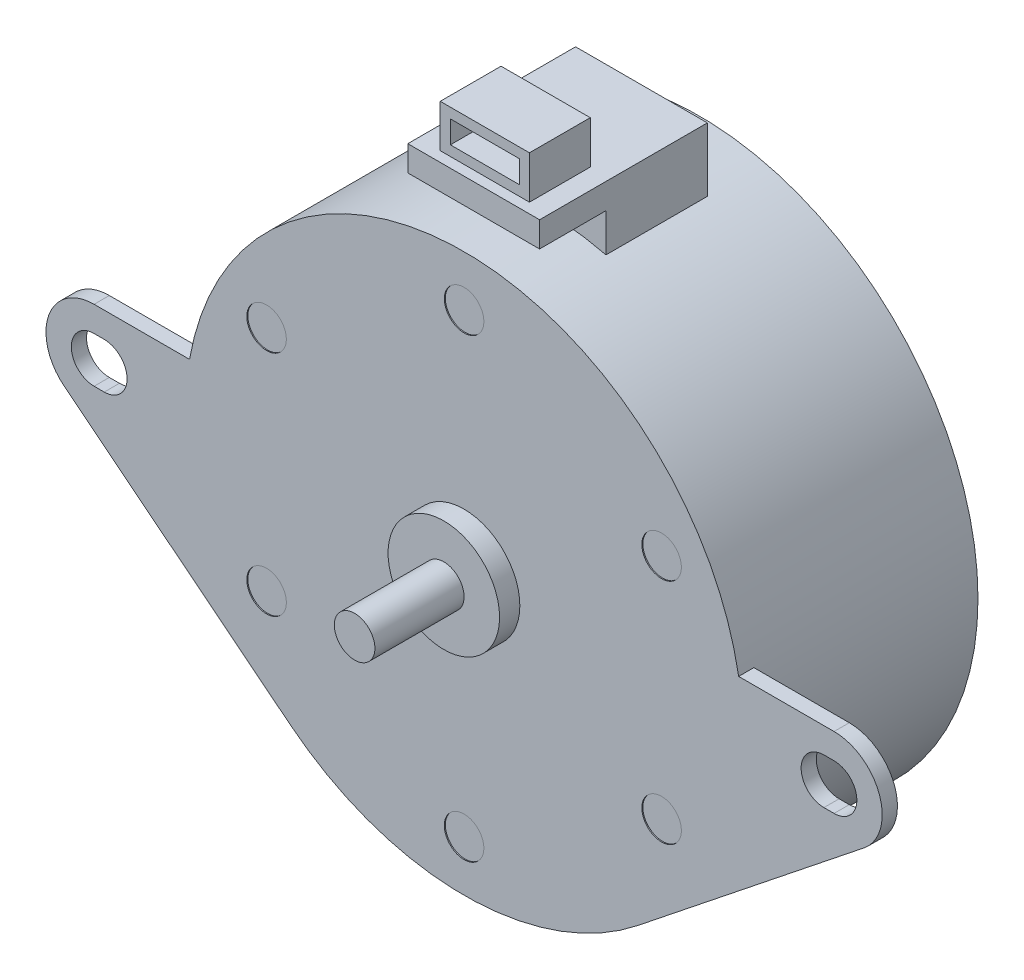
SolidWorks part; units mm, degrees
ref_plane "Front Plane" through (0, 0, 0) normal (0, 0, 1) x (1, 0, 0)
ref_plane "Top Plane" through (0, 0, 0) normal (0, 1, 0) x (1, 0, 0)
ref_plane "Right Plane" through (0, 0, 0) normal (1, 0, 0) x (0, 0, -1)
ref_plane "Plane1" through (0, 27.5, 0) normal (0, -1, 0) x (1, 0, 0)
sketch "Sketch1" plane through (0, 27.5, 0) normal (0, -1, 0) x (1, 0, 0)
  line L0 (55, 23.2) -> (27.5, 23.2)
  line L1 (27.5, 23.2) -> (27.5, 0)
  line L2 (27.5, 0) -> (55, 0)
  line L3 (55, 0) -> (55, 23.2)
  line L4 (27.5, 23.2) -> (27.5, 0) construction
revolve "Revolve1" add sketch "Sketch1" angle 360 about L4
ref_plane "Plane2" through (0, 60.5, 0) normal (0, 1, 0) x (1, 0, 0)
sketch "Sketch2" plane through (0, 60.5, 0) normal (0, 1, 0) x (1, 0, 0)
  line L0 (21, -5.7) -> (21, -15.7)
  line L1 (21, -15.7) -> (34, -15.7)
  line L2 (34, -15.7) -> (34, -5.7)
  line L3 (34, -5.7) -> (21, -5.7)
extrude "Boss-Extrude1" add sketch "Sketch2" against normal up to next
sketch "Sketch3" plane through (0, 0, 15.7) normal (0, 0, 1) x (1, 0, 0)
  line L0 (34, 60.5) -> (34, 58)
  line L1 (21, 58) -> (21, 60.5)
  line L2 (21, 60.5) -> (34, 60.5)
  spline S0 degree 1 poles (21, 58) (34, 58) knots 0 0 1 1
extrude "Boss-Extrude2" add sketch "Sketch3" along normal blind 6.5533
ref_plane "Plane3" through (0, 0, 23.2) normal (0, 0, 1) x (1, 0, 0)
sketch "Sketch4" plane through (0, 0, 23.2) normal (0, 0, 1) x (1, 0, 0)
  line L0 (64, 32.25) -> (54.5867, 32.25)
  line L1 (44.6404, 5.9952) -> (66.9606, 23.7855)
  arc A0 (66.9606, 23.7855) -> (64, 32.25) centre (64, 27.5) ccw
  arc A1 (54.5867, 32.25) -> (44.6404, 5.9952) centre (27.5, 27.5) cw
extrude "Boss-Extrude3" add sketch "Sketch4" against normal blind 1.5
sketch "Sketch5" plane through (0, 0, 23.2) normal (0, 0, 1) x (1, 0, 0)
  line L0 (-11.9606, 23.7855) -> (10.3596, 5.9952)
  line L1 (0.4133, 32.25) -> (-9, 32.25)
  arc A0 (-9, 32.25) -> (-11.9606, 23.7855) centre (-9, 27.5) ccw
  arc A1 (10.3596, 5.9952) -> (0.4133, 32.25) centre (27.5, 27.5) cw
extrude "Boss-Extrude4" add sketch "Sketch5" against normal blind 1.5
sketch "Sketch6" plane through (0, 0, 23.2) normal (0, 0, 1) x (1, 0, 0)
  line L0 (63, 25.25) -> (64, 25.25)
  line L1 (64, 29.75) -> (63, 29.75)
  arc A0 (63, 29.75) -> (63, 25.25) centre (63, 27.5) ccw
  arc A1 (64, 25.25) -> (64, 29.75) centre (64, 27.5) ccw
extrude "Cut-Extrude1" cut sketch "Sketch6" against normal through all
sketch "Sketch7" plane through (0, 0, 21.7) normal (0, 0, -1) x (-1, 0, 0)
  line L0 (8, 25.25) -> (9, 25.25)
  line L1 (9, 29.75) -> (8, 29.75)
  arc A0 (9, 25.25) -> (9, 29.75) centre (9, 27.5) ccw
  arc A1 (8, 29.75) -> (8, 25.25) centre (8, 27.5) ccw
extrude "Cut-Extrude2" cut sketch "Sketch7" against normal through all
sketch "Sketch8" plane through (0, 0, 23.2) normal (0, 0, 1) x (1, 0, 0)
  circle A0 centre (27.5, 27.5) radius 5.5
extrude "Boss-Extrude5" add sketch "Sketch8" along normal blind 2
sketch "Sketch9" plane through (0, 0, 25.2) normal (0, 0, 1) x (1, 0, 0)
  circle A0 centre (27.5, 27.5) radius 2
extrude "Boss-Extrude6" add sketch "Sketch9" along normal blind 8.8
sketch "Sketch10" plane through (0, 60.5, 0) normal (0, 1, 0) x (-1, 0, 0)
  line L0 (-23.2, 15.2533) -> (-32, 15.2533)
  line L1 (-32, 15.2533) -> (-32, 21.2533)
  line L2 (-32, 21.2533) -> (-23.2, 21.2533)
  line L3 (-23.2, 21.2533) -> (-23.2, 15.2533)
extrude "Boss-Extrude7" add sketch "Sketch10" along normal blind 4.22
sketch "Sketch11" plane through (0, 0, 21.2533) normal (0, 0, 1) x (1, 0, 0)
  line L0 (24.2, 61.5) -> (31, 61.5)
  line L1 (31, 61.5) -> (31, 63.72)
  line L2 (31, 63.72) -> (24.2, 63.72)
  line L3 (24.2, 63.72) -> (24.2, 61.5)
extrude "Cut-Extrude3" cut sketch "Sketch11" against normal blind 5
sketch "Sketch12" plane through (0, 0, 0) normal (0, 0, -1) x (-1, 0, 0)
  circle A0 centre (-27.5, 27.5) radius 19.15
extrude "Boss-Extrude8" add sketch "Sketch12" along normal blind 1.5 draft 45
hole_wizard "Ø7.0 (7) Diameter Hole1" positions "Sketch14" profile "Sketch13" hole size "Ø7.0" standard "ANSI Metric"
sketch "Sketch14" plane through (0, 0, -1.5) normal (0, 0, -1) x (-1, 0, 0)
  point P0 (-27.5, 27.5)
sketch "Sketch13" plane through (27.5, 27.5, -1.5) normal (1, 0, 0) x (0, 1, 0)
  line L0 (0, 0) -> (0, 1.5)
  line L1 (0, 1.5) -> (3.5, 1.5)
  line L2 (3.5, 1.5) -> (3.5, 0)
  line L5 (3.5, 0) -> (0, 0)
  line L10 (0, 1.5) -> (-3.5, 1.5) construction
  line L11 (0, -6.35) -> (0, 107.95) construction
  dimension "Hole Dia." = 7
  dimension "Hole Depth" = 1.5
  dimension "Drill Angle" = 180
ref_plane "Plane4" through (0, 16.25, 0) normal (0, 1, 0) x (1, 0, 0)
sketch "Sketch15" plane through (0, 16.25, 0) normal (0, 1, 0) x (1, 0, 0)
  line L0 (9.9644, -23.1) -> (8.0144, -23.1)
  line L1 (8.0144, -23.1) -> (8.0144, -23.2)
  line L2 (8.0144, -23.2) -> (9.9644, -23.2)
  line L3 (9.9644, -23.2) -> (9.9644, -23.1)
  line L4 (8.0144, -23.1) -> (8.0144, -23.2) construction
revolve "Cut-Revolve1" cut sketch "Sketch15" angle 360 about L4
ref_plane "Plane5" through (0, 5, 0) normal (0, 1, 0) x (1, 0, 0)
sketch "Sketch16" plane through (0, 5, 0) normal (0, 1, 0) x (1, 0, 0)
  line L0 (29.45, -23.1) -> (27.5, -23.1)
  line L1 (27.5, -23.1) -> (27.5, -23.2)
  line L2 (27.5, -23.2) -> (29.45, -23.2)
  line L3 (29.45, -23.2) -> (29.45, -23.1)
  line L4 (27.5, -23.1) -> (27.5, -23.2) construction
revolve "Cut-Revolve2" cut sketch "Sketch16" angle 360 about L4
sketch "Sketch17" plane through (0, 16.25, 0) normal (0, 1, 0) x (1, 0, 0)
  line L0 (48.9356, -23.1) -> (46.9856, -23.1)
  line L1 (46.9856, -23.1) -> (46.9856, -23.2)
  line L2 (46.9856, -23.2) -> (48.9356, -23.2)
  line L3 (48.9356, -23.2) -> (48.9356, -23.1)
  line L4 (46.9856, -23.1) -> (46.9856, -23.2) construction
revolve "Cut-Revolve3" cut sketch "Sketch17" angle 360 about L4
ref_plane "Plane6" through (0, 38.75, 0) normal (0, 1, 0) x (1, 0, 0)
sketch "Sketch18" plane through (0, 38.75, 0) normal (0, 1, 0) x (1, 0, 0)
  line L0 (48.9356, -23.1) -> (46.9856, -23.1)
  line L1 (46.9856, -23.1) -> (46.9856, -23.2)
  line L2 (46.9856, -23.2) -> (48.9356, -23.2)
  line L3 (48.9356, -23.2) -> (48.9356, -23.1)
  line L4 (46.9856, -23.1) -> (46.9856, -23.2) construction
revolve "Cut-Revolve4" cut sketch "Sketch18" angle 360 about L4
ref_plane "Plane7" through (0, 50, 0) normal (0, 1, 0) x (1, 0, 0)
sketch "Sketch19" plane through (0, 50, 0) normal (0, 1, 0) x (1, 0, 0)
  line L0 (29.45, -23.1) -> (27.5, -23.1)
  line L1 (27.5, -23.1) -> (27.5, -23.2)
  line L2 (27.5, -23.2) -> (29.45, -23.2)
  line L3 (29.45, -23.2) -> (29.45, -23.1)
  line L4 (27.5, -23.1) -> (27.5, -23.2) construction
revolve "Cut-Revolve5" cut sketch "Sketch19" angle 360 about L4
sketch "Sketch20" plane through (0, 38.75, 0) normal (0, 1, 0) x (1, 0, 0)
  line L0 (9.9644, -23.1) -> (8.0144, -23.1)
  line L1 (8.0144, -23.1) -> (8.0144, -23.2)
  line L2 (8.0144, -23.2) -> (9.9644, -23.2)
  line L3 (9.9644, -23.2) -> (9.9644, -23.1)
  line L4 (8.0144, -23.1) -> (8.0144, -23.2) construction
revolve "Cut-Revolve6" cut sketch "Sketch20" angle 360 about L4
ref_plane "Plane8" through (0, 27.5, 0) normal (0, 1, 0) x (1, 0, 0)
sketch "Sketch21" plane through (0, 27.5, 0) normal (0, 1, 0) x (1, 0, 0)
  line L0 (29.5, 7) -> (27.5, 7)
  line L1 (27.5, 7) -> (27.5, 0)
  line L2 (27.5, 0) -> (29.5, 0)
  line L3 (29.5, 0) -> (29.5, 7)
  line L4 (27.5, 7) -> (27.5, 0) construction
revolve "Revolve2" add sketch "Sketch21" angle 360 about L4
sketch "Sketch22" plane through (0, 16.25, 0) normal (0, 1, 0) x (1, 0, 0)
  line L0 (48.9356, 0.9) -> (46.9856, 0.9)
  line L1 (46.9856, 0.9) -> (46.9856, 0)
  line L2 (46.9856, 0) -> (48.9356, 0)
  line L3 (48.9356, 0) -> (48.9356, 0.9)
  line L4 (46.9856, 0.9) -> (46.9856, 0) construction
revolve "Revolve3" add sketch "Sketch22" angle 360 about L4
sketch "Sketch23" plane through (0, 5, 0) normal (0, 1, 0) x (1, 0, 0)
  line L0 (29.45, 0.9) -> (27.5, 0.9)
  line L1 (27.5, 0.9) -> (27.5, 0)
  line L2 (27.5, 0) -> (29.45, 0)
  line L3 (29.45, 0) -> (29.45, 0.9)
  line L4 (27.5, 0.9) -> (27.5, 0) construction
revolve "Revolve4" add sketch "Sketch23" angle 360 about L4
sketch "Sketch24" plane through (0, 16.25, 0) normal (0, 1, 0) x (1, 0, 0)
  line L0 (9.9644, 0.9) -> (8.0144, 0.9)
  line L1 (8.0144, 0.9) -> (8.0144, 0)
  line L2 (8.0144, 0) -> (9.9644, 0)
  line L3 (9.9644, 0) -> (9.9644, 0.9)
  line L4 (8.0144, 0.9) -> (8.0144, 0) construction
revolve "Revolve5" add sketch "Sketch24" angle 360 about L4
sketch "Sketch25" plane through (0, 38.75, 0) normal (0, 1, 0) x (1, 0, 0)
  line L0 (9.9644, 0.9) -> (8.0144, 0.9)
  line L1 (8.0144, 0.9) -> (8.0144, 0)
  line L2 (8.0144, 0) -> (9.9644, 0)
  line L3 (9.9644, 0) -> (9.9644, 0.9)
  line L4 (8.0144, 0.9) -> (8.0144, 0) construction
revolve "Revolve6" add sketch "Sketch25" angle 360 about L4
sketch "Sketch26" plane through (0, 50, 0) normal (0, 1, 0) x (1, 0, 0)
  line L0 (29.45, 0.9) -> (27.5, 0.9)
  line L1 (27.5, 0.9) -> (27.5, 0)
  line L2 (27.5, 0) -> (29.45, 0)
  line L3 (29.45, 0) -> (29.45, 0.9)
  line L4 (27.5, 0.9) -> (27.5, 0) construction
revolve "Revolve7" add sketch "Sketch26" angle 360 about L4
sketch "Sketch27" plane through (0, 38.75, 0) normal (0, 1, 0) x (1, 0, 0)
  line L0 (48.9356, 0.9) -> (46.9856, 0.9)
  line L1 (46.9856, 0.9) -> (46.9856, 0)
  line L2 (46.9856, 0) -> (48.9356, 0)
  line L3 (48.9356, 0) -> (48.9356, 0.9)
  line L4 (46.9856, 0.9) -> (46.9856, 0) construction
revolve "Revolve8" add sketch "Sketch27" angle 360 about L4
